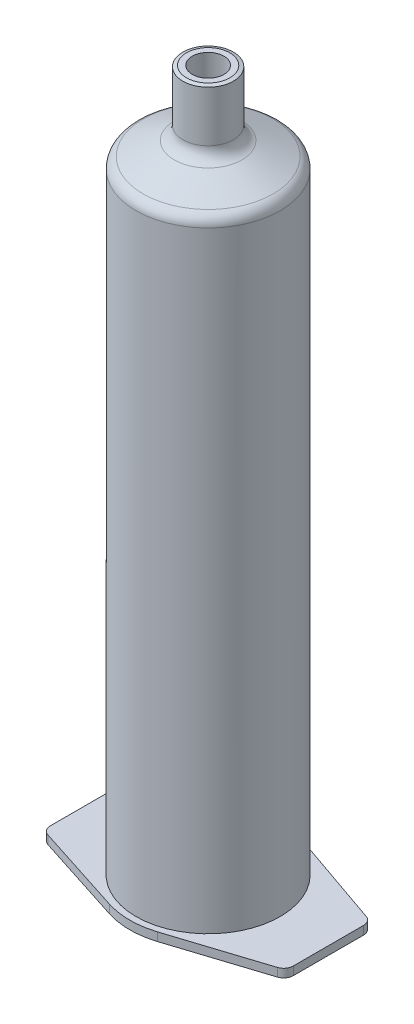
SolidWorks part; units mm, degrees
material "Acrylic (Medium-high impact)"
ref_plane "Front Plane" through (0, 0, 0) normal (0, 0, 1) x (1, 0, 0)
ref_plane "Top Plane" through (0, 0, 0) normal (0, 1, 0) x (1, 0, 0)
ref_plane "Right Plane" through (0, 0, 0) normal (1, 0, 0) x (0, 0, -1)
ref_plane "Plane1" through (0, -122, 0) normal (0, -1, 0) x (1, 0, 0)
sketch "Sketch1" plane through (0, -122, 0) normal (0, -1, 0) x (1, 0, 0)
  line L0 (0, -17.2512) -> (25.25, -8.5)
  line L1 (25.25, -8.5) -> (25.25, 9)
  line L2 (25.25, 9) -> (0, 17.1226)
  line L3 (0, 17.1226) -> (-25.25, 9)
  line L4 (-25.25, 9) -> (-25.25, -8.5)
  line L5 (-25.25, -8.5) -> (0, -17.2512)
extrude "Boss-Extrude1" add sketch "Sketch1" against normal blind 1.75
ref_plane "Plane2" through (0, 0, 0) normal (0, 0, -1) x (-1, 0, 0)
sketch "Sketch2" plane through (0, 0, 0) normal (0, 0, -1) x (-1, 0, 0)
  line L0 (-15, -120.25) -> (0, -120.25)
  line L1 (0, -120.25) -> (0, 50)
  line L2 (0, 50) -> (-3, 50)
  line L3 (-3, 50) -> (-4.5105, 25.5459)
  line L4 (-4.5105, 25.5459) -> (-5.25, 25.3081)
  line L5 (-5.25, 25.3081) -> (-5.25, 12.8081)
  line L6 (-5.25, 12.8081) -> (-15, 8.4748)
  line L7 (-15, 8.4748) -> (-15, -120.25)
  line L8 (0, -120.25) -> (0, 50) construction
revolve "Revolve1" add sketch "Sketch2" angle 360 about L8
sketch "Sketch3" plane through (0, 0, 0) normal (0, 0, -1) x (-1, 0, 0)
  line L0 (-14, -122) -> (0, -122)
  line L1 (0, -122) -> (0, 50)
  line L2 (0, 50) -> (-1.7, 50)
  line L3 (-1.7, 50) -> (-4.1659, 12.1957)
  line L4 (-4.1659, 12.1957) -> (-14, 7.8249)
  line L5 (-14, 7.8249) -> (-14, -122)
  line L6 (0, -122) -> (0, 50) construction
revolve "Cut-Revolve1" cut sketch "Sketch3" angle 360 about L6
fillet "Fillet1" radius 1 1 edges at (0, 50, 3)
fillet "Fillet2" radius 1.5 1 edges at (0, 7.8249, 14)
fillet "Fillet3" radius 2 4 edges at (25.25, -121.125, -8.5) (25.25, -121.125, 9) (-25.25, -121.125, -8.5) (-25.25, -121.125, 9)
fillet "Fillet4" radius 2.5 1 edges at (0, 8.4748, 15)
fillet "Fillet5" radius 3 1 edges at (0, 12.8081, 5.25)
fillet "Fillet6" radius 4 1 edges at (0, 12.1957, 4.1659)
fillet "Fillet7" radius 16.3 2 edges at (0, -121.125, -17.2512) (0, -121.125, 17.1226)
ref_plane "Plane3" through (0, 25.5459, 0) normal (0, -1, 0) x (-1, 0, 0)
sketch "Sketch4" plane through (0, 25.5459, 0) normal (0, -1, 0) x (-1, 0, 0)
  circle A0 centre (0, 0) radius 17.4473
extrude "Cut-Extrude1" cut sketch "Sketch4" against normal up to next
